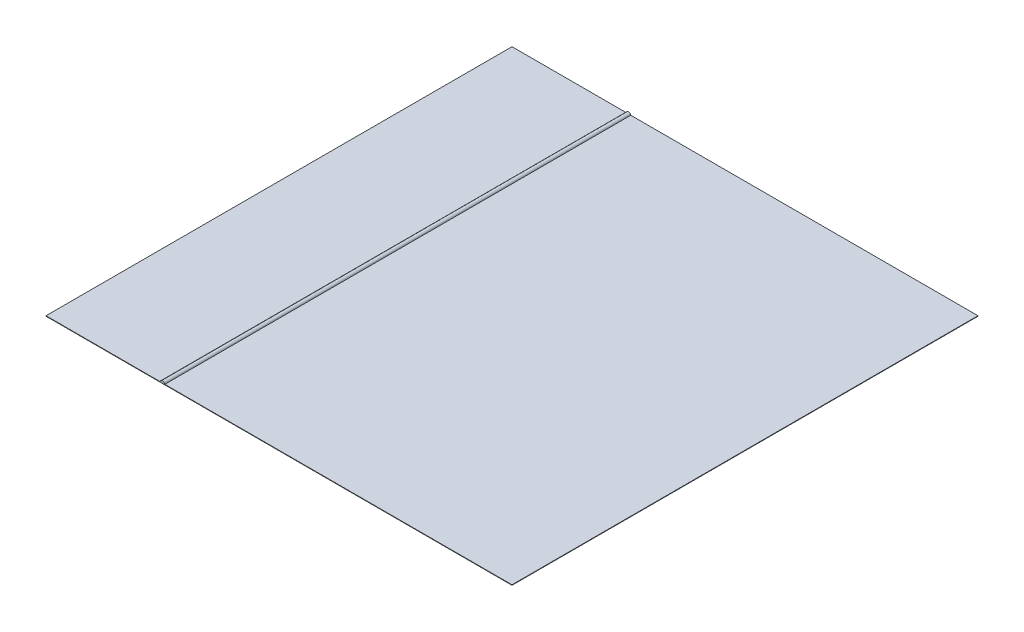
SolidWorks part; units mm, degrees
ref_plane "Front Plane" through (0, 0, 0) normal (0, 0, 1) x (1, 0, 0)
ref_plane "Top Plane" through (0, 0, 0) normal (0, 1, 0) x (1, 0, 0)
ref_plane "Right Plane" through (0, 0, 0) normal (1, 0, 0) x (0, 0, -1)
sketch "Sketch1" plane through (0, 0, 0) normal (0, 1, 0) x (1, 0, 0)
  line L1 (-5000, -5000) -> (5000, -5000)
  line L2 (-5000, -5000) -> (-5000, 5000)
  line L3 (-5000, 5000) -> (5000, 5000)
  line L4 (5000, -5000) -> (5000, 5000)
  line L5 (-5000, -5000) -> (5000, 5000) construction
  line L6 (-5000, 5000) -> (5000, -5000) construction
  point P0 (0, 0)
  dimension "D1" = 10000
  dimension "D2" = 10000
extrude "Boss-Extrude1" add sketch "Sketch1" along normal blind 10
sketch "Sketch4" plane through (0, 0, 5000) normal (0, 0, 1) x (1, 0, 0)
  line L0 (-5000, 0) -> (5000, 0) construction
  line L1 (-5000, 10) -> (-5000, 0) construction
  line L2 (-2451.0102, 10) -> (-2548.9898, 10)
  line L3 (-5000, 10) -> (5000, 10) construction
  arc A0 (-2451.0102, 10) -> (-2548.9898, 10) centre (-2500, 0) ccw
  dimension "D1" = 2500
extrude "Boss-Extrude3" add sketch "Sketch4" against normal up to surface (10000 mm away) up to face at (0, 5, -5000)
